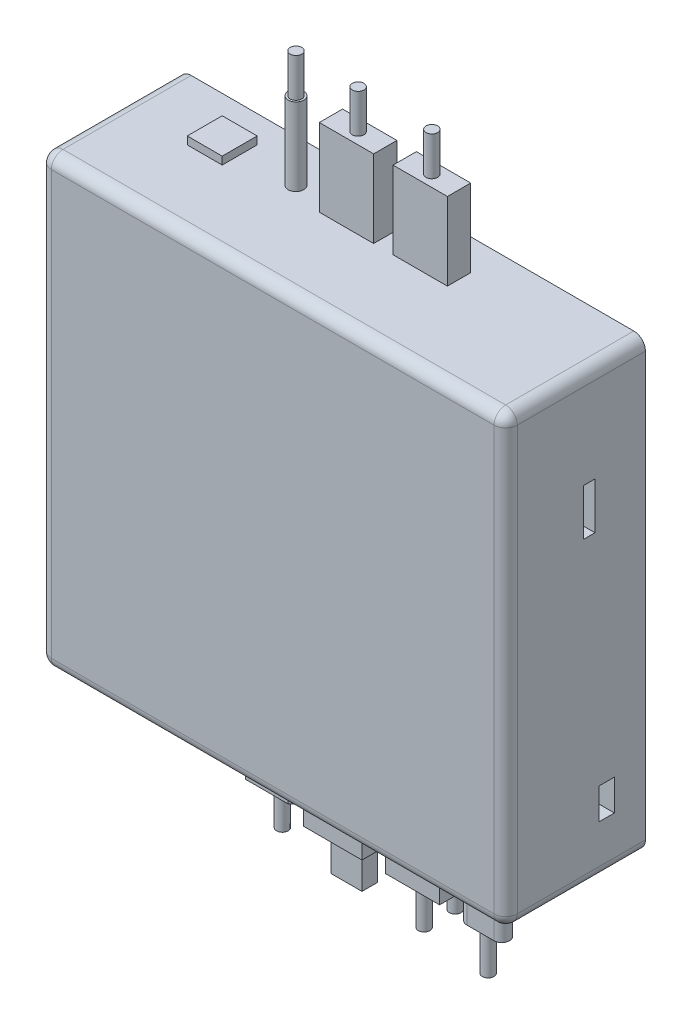
SolidWorks part; units mm, degrees
ref_plane "前视基准面" through (0, 0, 0) normal (0, 0, 1) x (1, 0, 0)
ref_plane "上视基准面" through (0, 0, 0) normal (0, 1, 0) x (1, 0, 0)
ref_plane "右视基准面" through (0, 0, 0) normal (1, 0, 0) x (0, 0, -1)
sketch "草图1" plane through (0, 0, 0) normal (0, 0, 1) x (1, 0, 0)
  line L1 (60, -57.5) -> (-60, -57.5)
  line L2 (60, -57.5) -> (60, 57.5)
  line L3 (60, 57.5) -> (-60, 57.5)
  line L4 (-60, -57.5) -> (-60, 57.5)
  line L5 (60, -57.5) -> (-60, 57.5) construction
  line L6 (60, 57.5) -> (-60, -57.5) construction
  point P0 (0, 0)
  dimension "D1" = 120
  dimension "D2" = 115
extrude "凸台-拉伸1" add sketch "草图1" along normal blind 36
sketch "草图2" plane through (0, 0, 0) normal (0, 0, -1) x (-1, 0, 0)
  circle A0 centre (0, 42) radius 1.5
  circle A1 centre (0, -42) radius 1.5
  dimension "D3" = 3
  dimension "D4" = 3
  dimension "D1" = 42
  dimension "D2" = 42
extrude "切除-拉伸1" cut sketch "草图2" against normal blind 6
fillet "圆角1" radius 3 8 edges at (0, 57.5, 36) (60, 0, 36) (0, -57.5, 36) (-60, 0, 36) (-60, -57.5, 18) (-60, 57.5, 18) (60, 57.5, 18) (60, -57.5, 18)
sketch "草图3" plane through (0, -57.5, 0) normal (0, -1, 0) x (1, 0, 0)
  line L0 (-60, 0) -> (-60, 33) construction
  line L1 (-57, 0) -> (57, 0) construction
  line L2 (-30, 13) -> (-28, 15)
  line L3 (-28, 15) -> (-17, 15)
  line L4 (-30, 13) -> (-30, 8)
  line L5 (-30, 8) -> (-15, 8)
  line L6 (-15, 13) -> (-15, 8)
  line L7 (-17, 15) -> (-15, 13)
  line L8 (0, 8) -> (5, 8)
  line L9 (-10, 18) -> (5, 18)
  line L10 (-10, 18) -> (-10, 8)
  line L11 (-10, 8) -> (-5, 8)
  line L12 (5, 18) -> (5, 8)
  line L14 (-5, 8) -> (-5, 6.5)
  line L15 (-5, 6.5) -> (0, 6.5)
  line L16 (0, 8) -> (0, 6.5)
  line L17 (33, 17) -> (40, 17) construction
  line L18 (11, 18) -> (25, 18)
  line L19 (11, 18) -> (11, 12)
  line L20 (11, 12) -> (25, 12)
  line L21 (25, 18) -> (25, 12)
  line L22 (11, 10) -> (25, 10)
  line L23 (11, 10) -> (11, 4)
  line L24 (11, 4) -> (25, 4)
  line L25 (25, 10) -> (25, 4)
  line L30 (33, 19) -> (40, 19)
  line L31 (33, 15) -> (40, 15)
  circle A0 centre (-40, 10) radius 3.5
  arc A5 (33, 19) -> (33, 15) centre (33, 17) ccw
  arc A6 (40, 15) -> (40, 19) centre (40, 17) ccw
  point P6 (-30, 15)
  point P9 (-15, 15)
  point P33 (36.5, 17)
  dimension "D1" = 20
  dimension "D2" = 10
  dimension "D3" = 7
  dimension "D25" = 3
  dimension "D27" = 7
  dimension "D26" = 2
  dimension "D28" = 8
  dimension "D4" = 8
  dimension "D5" = 15
  dimension "D6" = 7
  dimension "D7" = 10
  dimension "D8" = 10
  dimension "D9" = 15
  dimension "D12" = 5
  dimension "D13" = 8
  dimension "D14" = 1.5
  dimension "D15" = 5
  dimension "D16" = 5
  dimension "D17" = 4
  dimension "D18" = 6
  dimension "D19" = 6
  dimension "D20" = 14
  dimension "D21" = 14
  dimension "D22" = 2
  dimension "D23" = 6
  dimension "D24" = 6
extrude "凸台-拉伸2" add sketch "草图3" along normal blind 20
sketch "草图4" plane through (0, -77.5, 0) normal (0, -1, 0) x (1, 0, 0)
  line L0 (-30, 8) -> (-15, 8) construction
  line L1 (-15, 8) -> (-15, 13) construction
  line L2 (5, 8) -> (5, 18) construction
  line L3 (-6, 15) -> (2, 15)
  line L4 (-6, 15) -> (-6, 11)
  line L5 (-6, 11) -> (2, 11)
  line L6 (2, 15) -> (2, 11)
  line L7 (-10, 8) -> (-5, 8) construction
  line L8 (25, 18) -> (11, 18) construction
  line L9 (11, 18) -> (11, 12) construction
  line L10 (25, 4) -> (25, 10) construction
  line L11 (25, 10) -> (11, 10) construction
  line L12 (40, 19) -> (33, 19) construction
  circle A0 centre (-22.5, 11) radius 1.5
  circle A1 centre (18, 15) radius 1.5
  circle A2 centre (18, 7) radius 1.5
  circle A3 centre (36.5, 17) radius 1.5
  arc A4 (33, 19) -> (33, 15) centre (33, 17) ccw construction
  dimension "D1" = 3
  dimension "D2" = 3
  dimension "D3" = 7.5
  dimension "D8" = 3
  dimension "D9" = 3
  dimension "D10" = 7
  dimension "D11" = 7
  dimension "D12" = 3
  dimension "D13" = 3
  dimension "D14" = 3
  dimension "D15" = 2
  dimension "D16" = 3.5
  dimension "D4" = 8
  dimension "D5" = 3
  dimension "D6" = 3
  dimension "D7" = 4
extrude "凸台-拉伸3" add sketch "草图4" along normal blind 10
sketch "草图5" plane through (60, 0, 0) normal (1, 0, 0) x (0, 0, -1)
  line L0 (0, -54.5) -> (0, 54.5) construction
  line L1 (-16, 32.5) -> (-13, 32.5)
  line L2 (-16, 32.5) -> (-16, 20.5)
  line L3 (-16, 20.5) -> (-13, 20.5)
  line L4 (-13, 32.5) -> (-13, 20.5)
  line L5 (-33, 57.5) -> (0, 57.5) construction
  line L6 (0, -57.5) -> (-33, -57.5) construction
  line L7 (-12, -36.5) -> (-8, -36.5)
  line L8 (-12, -36.5) -> (-12, -44.5)
  line L9 (-12, -44.5) -> (-8, -44.5)
  line L10 (-8, -36.5) -> (-8, -44.5)
  dimension "D1" = 12
  dimension "D2" = 13
  dimension "D3" = 3
  dimension "D4" = 25
  dimension "D5" = 8
  dimension "D6" = 4
  dimension "D7" = 13
  dimension "D8" = 8
extrude "切除-拉伸2" cut sketch "草图5" against normal blind 10
sketch "草图6" plane through (0, 57.5, 0) normal (0, 1, 0) x (1, 0, 0)
  line L0 (57, 0) -> (-57, 0) construction
  line L1 (-42, -7) -> (-33, -7)
  line L2 (-42, -7) -> (-42, -16)
  line L3 (-42, -16) -> (-33, -16)
  line L4 (-33, -7) -> (-33, -16)
  line L5 (-60, -33) -> (-60, 0) construction
  dimension "D1" = 9
  dimension "D2" = 9
  dimension "D3" = 7
  dimension "D4" = 18
extrude "凸台-拉伸4" add sketch "草图6" along normal blind 2
sketch "草图7" plane through (0, 57.5, 0) normal (0, 1, 0) x (1, 0, 0)
  line L0 (57, 0) -> (-57, 0) construction
  line L1 (-10, -8) -> (4, -8)
  line L2 (-10, -8) -> (-10, -14)
  line L3 (-10, -14) -> (4, -14)
  line L4 (4, -8) -> (4, -14)
  line L5 (9, -8) -> (23, -8)
  line L6 (9, -8) -> (9, -14)
  line L7 (9, -14) -> (23, -14)
  line L8 (23, -8) -> (23, -14)
  line L9 (-33, -16) -> (-33, -7) construction
  line L11 (-42, -16) -> (-33, -16) construction
  circle A0 centre (-19, -11) radius 2
  dimension "D9" = 4
  dimension "D10" = 9
  dimension "D11" = 5
  dimension "D1" = 6
  dimension "D2" = 6
  dimension "D3" = 14
  dimension "D4" = 14
  dimension "D5" = 5
  dimension "D6" = 8
  dimension "D7" = 14
  dimension "D8" = 23
extrude "凸台-拉伸5" add sketch "草图7" along normal blind 20 separate body
sketch "草图9" plane through (0, 77.5, 0) normal (0, 1, 0) x (1, 0, 0)
  line L0 (4, -8) -> (-10, -8) construction
  line L1 (4, -14) -> (4, -8) construction
  line L2 (9, -8) -> (9, -14) construction
  line L3 (9, -14) -> (23, -14) construction
  circle A0 centre (-3, -11) radius 1.5
  circle A1 centre (16, -11) radius 1.5
  circle A2 centre (-19, -11) radius 1.5
  dimension "D1" = 3
  dimension "D2" = 3
  dimension "D3" = 3
  dimension "D4" = 7
  dimension "D5" = 7
  dimension "D6" = 3
  dimension "D7" = 3
extrude "凸台-拉伸6" add sketch "草图9" along normal blind 10
sketch "草图10" plane through (0, 0, 0) normal (0, 0, -1) x (-1, 0, 0)
  line L0 (-58, 55.5) -> (58, 55.5)
  line L1 (-60, 57.5) -> (60, 57.5)
  line L2 (-60, 57.5) -> (-60, -57.5)
  line L3 (-60, -57.5) -> (60, -57.5)
  line L4 (60, 57.5) -> (60, -57.5)
  line L5 (58, 55.5) -> (58, -55.5)
  line L6 (-58, -55.5) -> (58, -55.5)
  line L7 (-58, 55.5) -> (-58, -55.5)
  circle A0 centre (-50, 47.5) radius 5
  circle A1 centre (50, 47.5) radius 5
  circle A2 centre (-50, -47.5) radius 5
  circle A3 centre (50, -47.5) radius 5
  circle M5 centre (0, -42) radius 1.5
  circle M6 centre (0, 42) radius 1.5
  dimension "D6" = 10
  dimension "D7" = 10
  dimension "D8" = 10
  dimension "D9" = 10
  dimension "D10" = 10
  dimension "D11" = 10
  dimension "D12" = 10
  dimension "D13" = 10
  dimension "D14" = 10
  dimension "D15" = 10
  dimension "D16" = 10
  dimension "D17" = 10
  dimension "D1" = 120
  dimension "D2" = 57.5
  dimension "D3" = 57.5
  dimension "D4" = 60
  dimension "D5" = 2
extrude "切除-拉伸3" cut sketch "草图10" against normal blind 5 contours L0 L7 L6 L5 A3 A2 A1 A0 M5 M6
